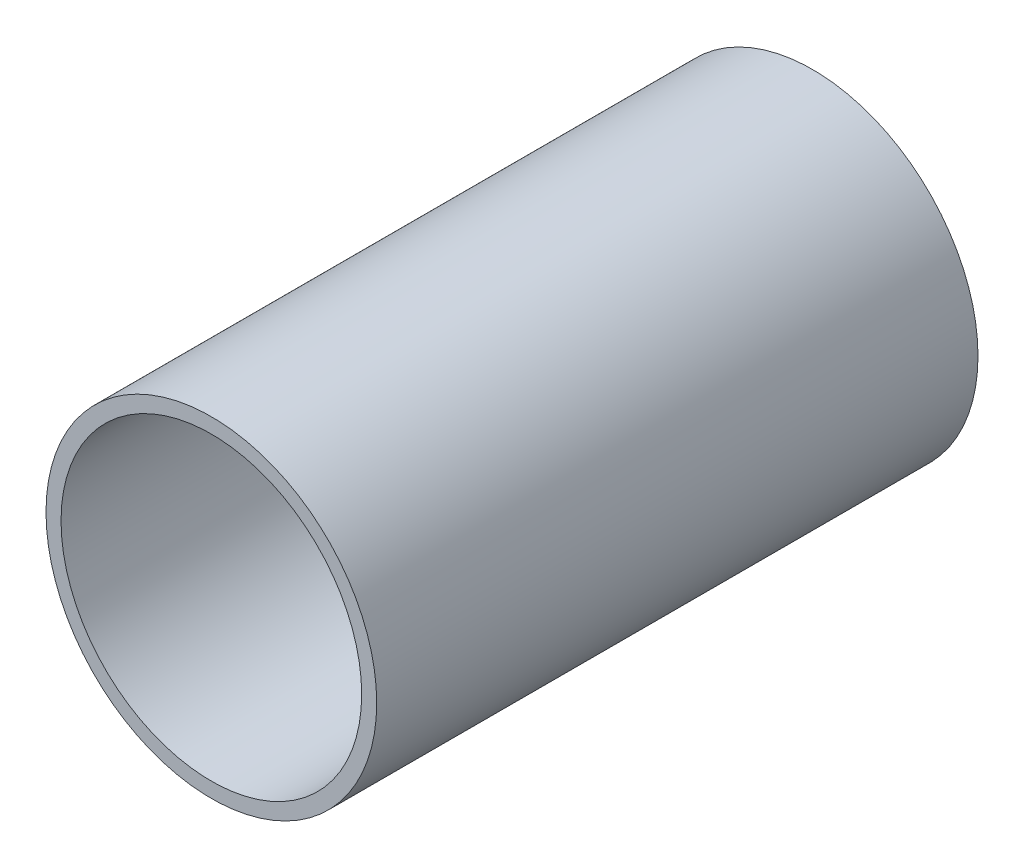
SolidWorks part; units mm, degrees
ref_plane "Front Plane" through (0, 0, 0) normal (0, 0, 1) x (1, 0, 0)
ref_plane "Top Plane" through (0, 0, 0) normal (0, 1, 0) x (1, 0, 0)
ref_plane "Right Plane" through (0, 0, 0) normal (1, 0, 0) x (0, 0, -1)
sketch "Sketch1" plane through (0, 0, 0) normal (0, 0, 1) x (1, 0, 0)
  circle A0 centre (0, 0) radius 419.1
  circle A1 centre (0, 0) radius 381
  dimension "D1" = 838.2
  dimension "D2" = 762
extrude "Boss-Extrude1" add sketch "Sketch1" along normal mid plane 1524
